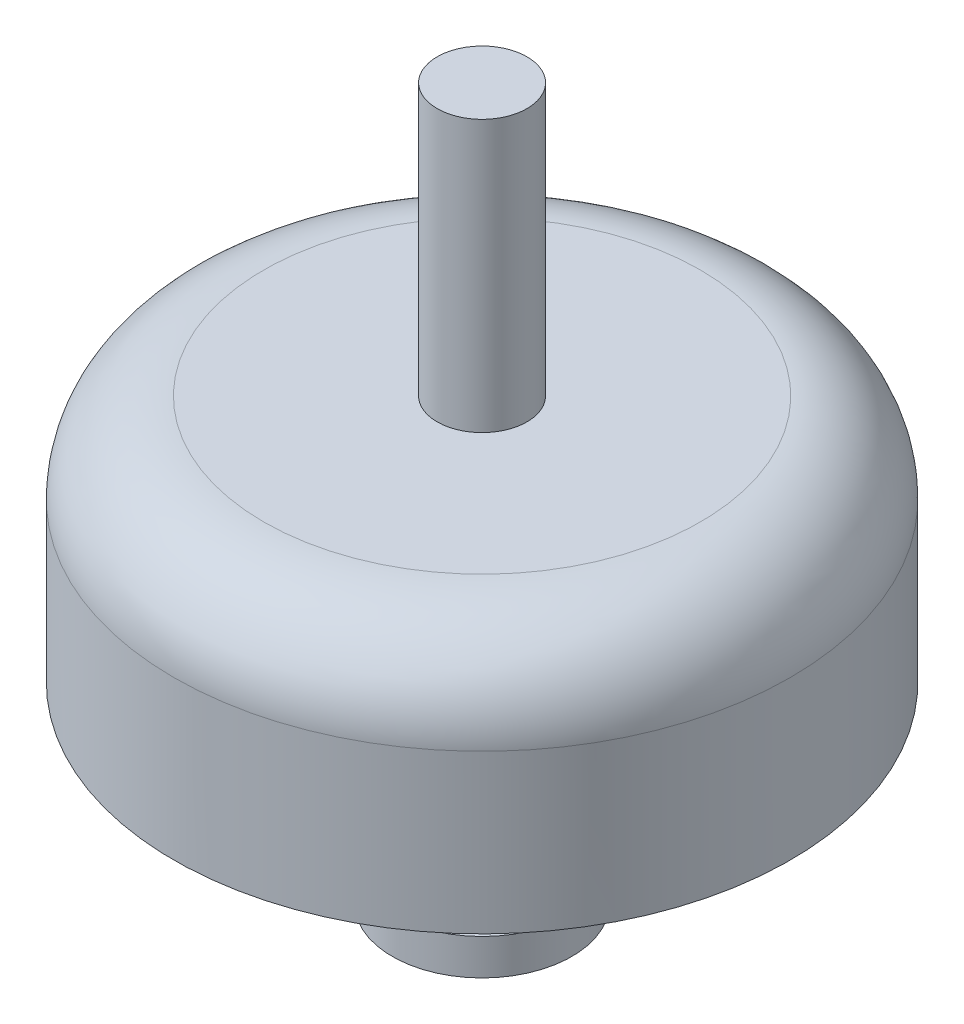
SolidWorks part; units mm, degrees
ref_plane "前视基准面" through (0, 0, 0) normal (0, 0, 1) x (1, 0, 0)
ref_plane "上视基准面" through (0, 0, 0) normal (0, 1, 0) x (1, 0, 0)
ref_plane "右视基准面" through (0, 0, 0) normal (1, 0, 0) x (0, 0, -1)
sketch "草图1" plane through (0, 0, 0) normal (0, 1, 0) x (1, 0, 0)
  line L0 (0, 0) -> (0, 5.6932) construction
  line L1 (11.7175, -11.7175) -> (-11.7175, -11.7175) construction
  line L2 (11.7175, -11.7175) -> (11.7175, 11.7175) construction
  line L3 (11.7175, 11.7175) -> (-11.7175, 11.7175) construction
  line L4 (-11.7175, -11.7175) -> (-11.7175, 11.7175) construction
  line L5 (11.7175, -11.7175) -> (-11.7175, 11.7175) construction
  line L6 (11.7175, 11.7175) -> (-11.7175, -11.7175) construction
  line L7 (0, 0) -> (5.306, 0) construction
  circle A0 centre (0, 0) radius 9.5 construction
  circle A5 centre (-6.7175, 6.7175) radius 1.5
  circle A6 centre (6.7175, 6.7175) radius 1.5
  circle A7 centre (6.7175, -6.7175) radius 1.5
  circle A8 centre (-6.7175, -6.7175) radius 1.5
  arc A9 (-2.7066, 9.7029) -> (-9.7029, 2.7066) centre (-6.7175, 6.7175) ccw
  arc A10 (2.7066, 9.7029) -> (9.7029, 2.7066) centre (6.7175, 6.7175) cw
  arc A11 (-2.7066, -9.7029) -> (-9.7029, -2.7066) centre (-6.7175, -6.7175) cw
  arc A12 (2.7066, -9.7029) -> (9.7029, -2.7066) centre (6.7175, -6.7175) ccw
  arc A13 (-2.7066, 9.7029) -> (2.7066, 9.7029) centre (0, 11.7175) ccw
  arc A14 (-2.7066, -9.7029) -> (2.7066, -9.7029) centre (0, -11.7175) cw
  arc A15 (-9.7029, -2.7066) -> (-9.7029, 2.7066) centre (-11.7175, 0) ccw
  arc A16 (9.7029, -2.7066) -> (9.7029, 2.7066) centre (11.7175, 0) cw
  point P0 (0, 0)
  dimension "D1" = 19
  dimension "D2" = 3
  dimension "D3" = 10
extrude "凸台-拉伸1" add sketch "草图1" along normal blind 2
sketch "草图2" plane through (0, 2, 0) normal (0, 1, 0) x (1, 0, 0)
  circle A0 centre (0, 0) radius 7
  dimension "D1" = 14
extrude "凸台-拉伸2" add sketch "草图2" along normal blind 2
sketch "草图3" plane through (0, 4, 0) normal (0, 1, 0) x (1, 0, 0)
  circle A0 centre (0, 0) radius 17.15
  dimension "D1" = 34.3
extrude "凸台-拉伸3" add sketch "草图3" along normal blind 13.8
fillet "圆角1" radius 5 1 edges at (0, 17.8, 17.15)
sketch "草图4" plane through (0, 17.8, 0) normal (0, 1, 0) x (1, 0, 0)
  circle A0 centre (0, 0) radius 2.5
  dimension "D1" = 5
extrude "凸台-拉伸4" add sketch "草图4" along normal blind 15.1
